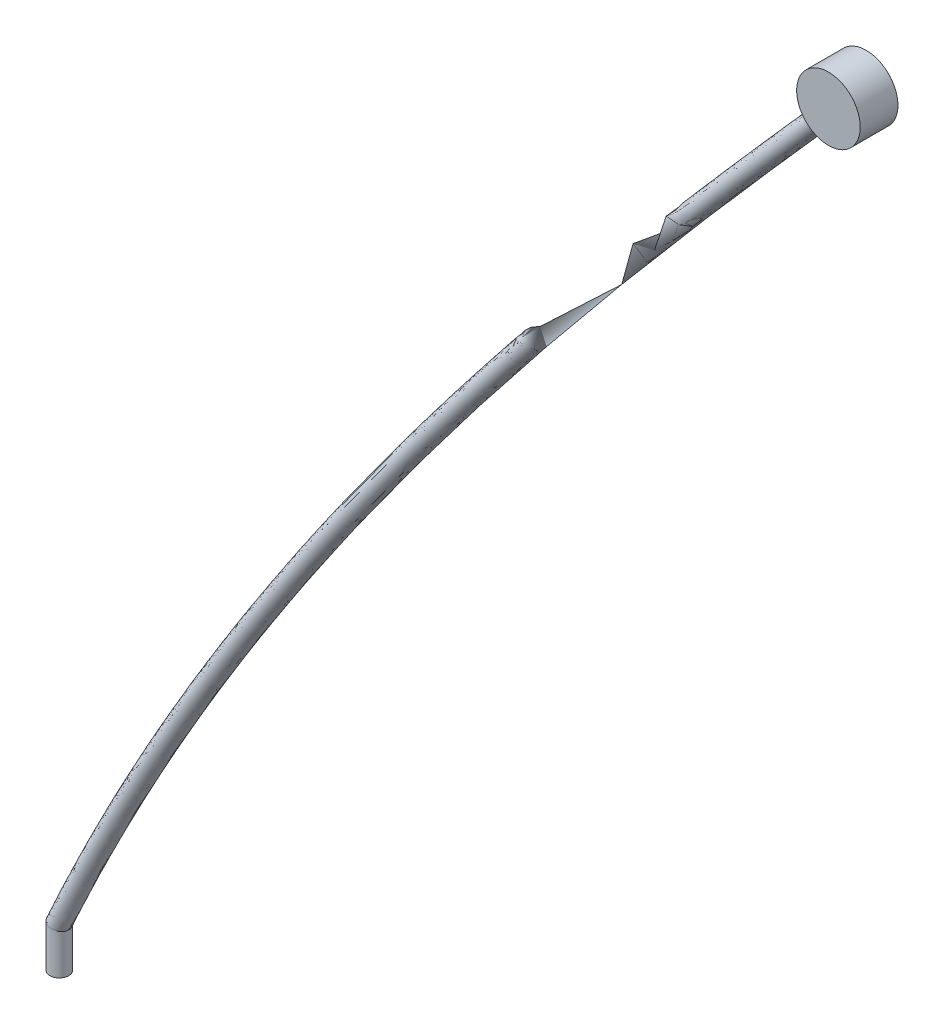
SolidWorks part; units mm, degrees
ref_plane "Front Plane" through (0, 0, 0) normal (0, 0, 1) x (1, 0, 0)
ref_plane "Top Plane" through (0, 0, 0) normal (0, 1, 0) x (1, 0, 0)
ref_plane "Right Plane" through (0, 0, 0) normal (1, 0, 0) x (0, 0, -1)
sketch "Sketch1" plane through (0, 0, 0) normal (0, 0, 1) x (1, 0, 0)
  line L0 (0, 0) -> (0, -2.2122)
  spline S0 degree 3 poles (0, 0) (9.7622, 21.5287) (25.2998, 40.2191) (40.8545, 57.6891) knots 0 0 0 0 1 1 1 1
sweep "Sweep1" add path "Sketch1" circular profile diameter 1 parameters "D3"=1
sketch "Sketch22" plane through (0, 0, 0) normal (0, 0, 1) x (1, 0, 0)
  circle A0 centre (41.7926, 58.7594) radius 1.6864
  point P2 (41.7926, 58.7594)
extrude "Boss-Extrude1" add sketch "Sketch22" along normal mid plane 2
